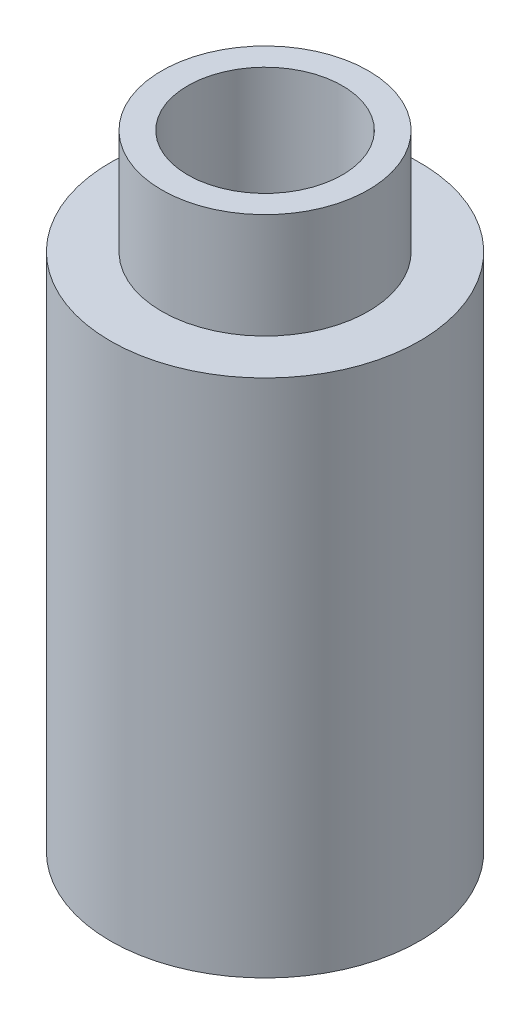
SolidWorks part; units mm, degrees
ref_plane "Front Plane" through (0, 0, 0) normal (0, 0, 1) x (1, 0, 0)
ref_plane "Top Plane" through (0, 0, 0) normal (0, 1, 0) x (1, 0, 0)
ref_plane "Right Plane" through (0, 0, 0) normal (1, 0, 0) x (0, 0, -1)
sketch "Sketch1" plane through (0, 0, 0) normal (0, 1, 0) x (1, 0, 0)
  circle A0 centre (0, 0) radius 9.4488
  dimension "D1" = 18.8976
extrude "Boss-Extrude1" add sketch "Sketch1" along normal blind 31.75
sketch "Sketch2" plane through (0, 31.75, 0) normal (0, 1, 0) x (1, 0, 0)
  circle A0 centre (0, 0) radius 6.3119
  dimension "D1" = 12.6238
extrude "Boss-Extrude2" add sketch "Sketch2" along normal blind 6.4262
sketch "Sketch3" plane through (0, 38.1762, 0) normal (0, 1, 0) x (1, 0, 0)
  circle A0 centre (0, 0) radius 4.7244
  dimension "D1" = 9.4488
extrude "Cut-Extrude1" cut sketch "Sketch3" against normal through all
